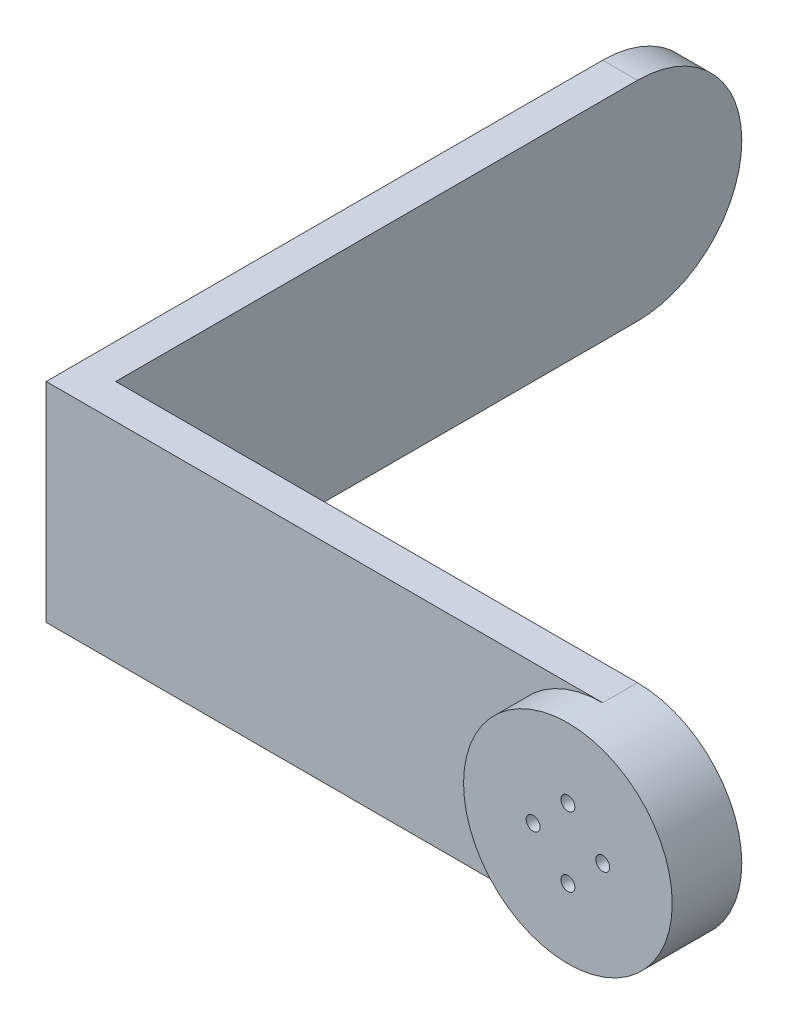
SolidWorks part; units mm, degrees
ref_plane "Front Plane" through (0, 0, 0) normal (0, 0, 1) x (1, 0, 0)
ref_plane "Top Plane" through (0, 0, 0) normal (0, 1, 0) x (1, 0, 0)
ref_plane "Right Plane" through (0, 0, 0) normal (1, 0, 0) x (0, 0, -1)
sketch "Sketch1" plane through (0, 0, 0) normal (0, 0, 1) x (1, 0, 0)
  circle A0 centre (0, 0) radius 15
  dimension "D1" = 30
extrude "face" add sketch "Sketch1" along normal blind 5
sketch "Sketch2" plane through (0, 0, 0) normal (0, 0, 1) x (1, 0, 0)
  line L1 (0, 15) -> (-80, 15)
  line L2 (0, 15) -> (0, -15)
  line L3 (0, -15) -> (-80, -15)
  line L4 (-80, 15) -> (-80, -15)
  circle A0 centre (0, 0) radius 15 construction
  circle A1 centre (0, 0) radius 15
  dimension "D2" = 30
  dimension "D1" = 80
extrude "L link" add sketch "Sketch2" against normal blind 5 contours A1 L1 L4 L3 | L2 A1 | L2 A1
sketch "Sketch3" plane through (0, 0, 5) normal (0, 0, 1) x (1, 0, 0)
  circle A0 centre (0, 5) radius 1
  circle A1 centre (5, 0) radius 1
  circle A2 centre (0, -5) radius 1
  circle A3 centre (-5, 0) radius 1
  point P2 (-5.2193, -4.9022)
  point P4 (0, 0)
  point P5 (0, 0)
  point P12 (0, -4.4759)
  point P13 (0, 0)
  dimension "D1" = 2
  dimension "D2" = 5
  dimension "D3" = 4
extrude "fixing screws " cut sketch "Sketch3" against normal through all
ref_plane "Plane1" through (-37.5, 0, 37.5) normal (0.7071, 0, -0.7071) x (-0.7071, 0, -0.7071)
ref_plane "Plane2" through (-40, 0, -40) normal (0.7071, 0, 0.7071) x (0.7071, 0, -0.7071)
mirror "Mirror2" about plane through (-40, 0, -40) normal (0.7071, 0, 0.7071) of "L link"
